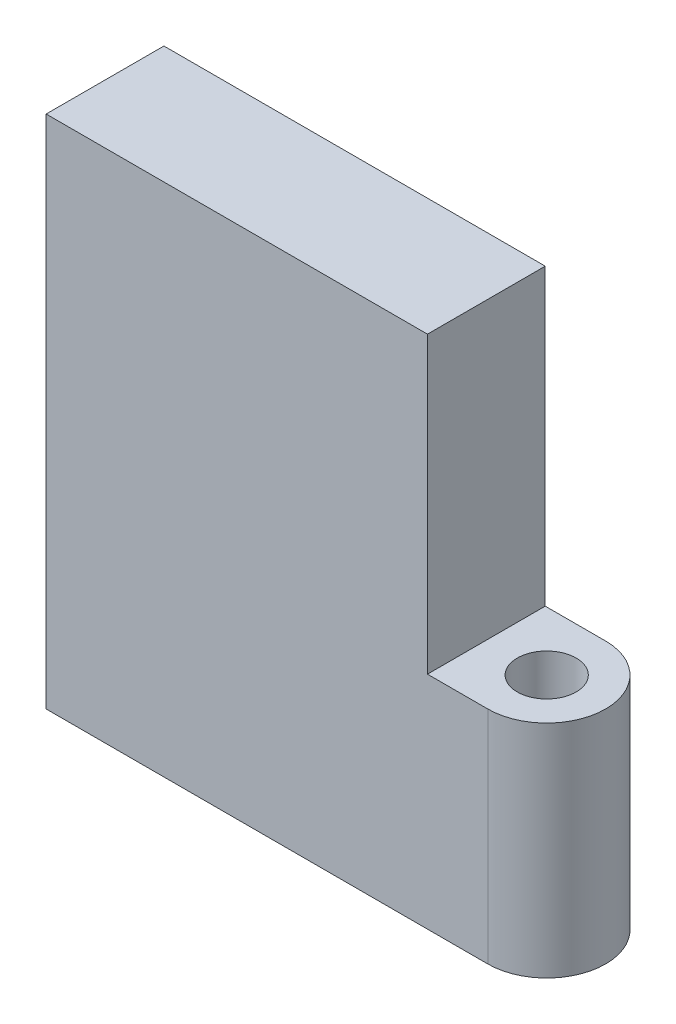
SolidWorks part; units mm, degrees
ref_plane "Front Plane" through (0, 0, 0) normal (0, 0, 1) x (1, 0, 0)
ref_plane "Top Plane" through (0, 0, 0) normal (0, 1, 0) x (1, 0, 0)
ref_plane "Right Plane" through (0, 0, 0) normal (1, 0, 0) x (0, 0, -1)
sketch "Sketch2" plane through (0, 0, 0) normal (0, 1, 0) x (1, 0, 0)
  line L1 (0, -4) -> (-30, -4)
  line L2 (0, -4) -> (0, 4)
  line L3 (0, 4) -> (-30, 4)
  line L4 (-30, -4) -> (-30, 4)
  circle A0 centre (0, 0) radius 4
  point P7 (0, 0)
  dimension "D1" = 8
  dimension "D3" = 8
  dimension "D2" = 30
extrude "Boss-Extrude1" add sketch "Sketch2" along normal blind 15 contours A0 L3 L4 L1 | L2 A0 | L2 A0
sketch "Sketch3" plane through (0, 15, 0) normal (0, 1, 0) x (1, 0, 0)
  circle A0 centre (0, 0) radius 2
extrude "Cut-Extrude1" cut sketch "Sketch3" against normal blind 12.5
sketch "Sketch4" plane through (0, 15, 0) normal (0, 1, 0) x (1, 0, 0)
  line L0 (0, -4) -> (-30, -4) construction
  line L1 (-30, 4) -> (-4.1, 4)
  line L2 (-30, 4) -> (-30, -4)
  line L3 (-30, -4) -> (-4.1, -4)
  line L4 (-4.1, 4) -> (-4.1, -4)
  point P7 (-4.1, 0)
  dimension "D1" = 4.1
extrude "Boss-Extrude2" add sketch "Sketch4" along normal blind 20
